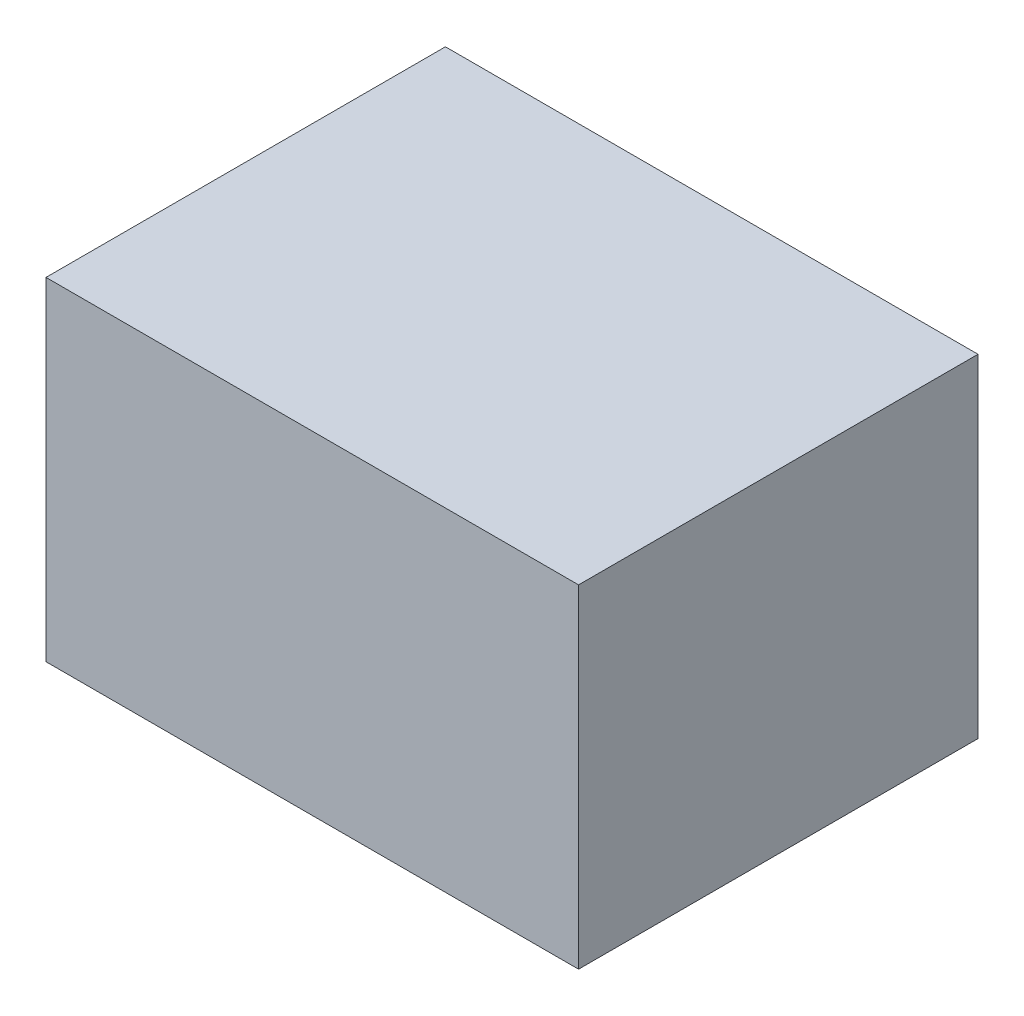
SolidWorks part; units mm, degrees
ref_plane "Front Plane" through (0, 0, 0) normal (0, 0, 1) x (1, 0, 0)
ref_plane "Top Plane" through (0, 0, 0) normal (0, 1, 0) x (1, 0, 0)
ref_plane "Right Plane" through (0, 0, 0) normal (1, 0, 0) x (0, 0, -1)
sketch "Sketch1" plane through (0, 0, 0) normal (0, 0, 1) x (1, 0, 0)
  line L0 (-1, -0.65) -> (-1, 0.6)
  line L1 (-1, 0.6) -> (1, 0.6)
  line L2 (1, 0.6) -> (1, -0.65)
  line L3 (1, -0.65) -> (-1, -0.65)
extrude "Component_Outline" add sketch "Sketch1" along normal blind 1.5 separate body
sketch3d "3DSketch1"
  line L0 (0, 0, 0) -> (1, 0, 0)
  line L1 (0, 0, 0) -> (0, 1, 0)
  line L2 (0, 0, 0) -> (0, 0, 1)
  point P0 (0, 0, 0)
